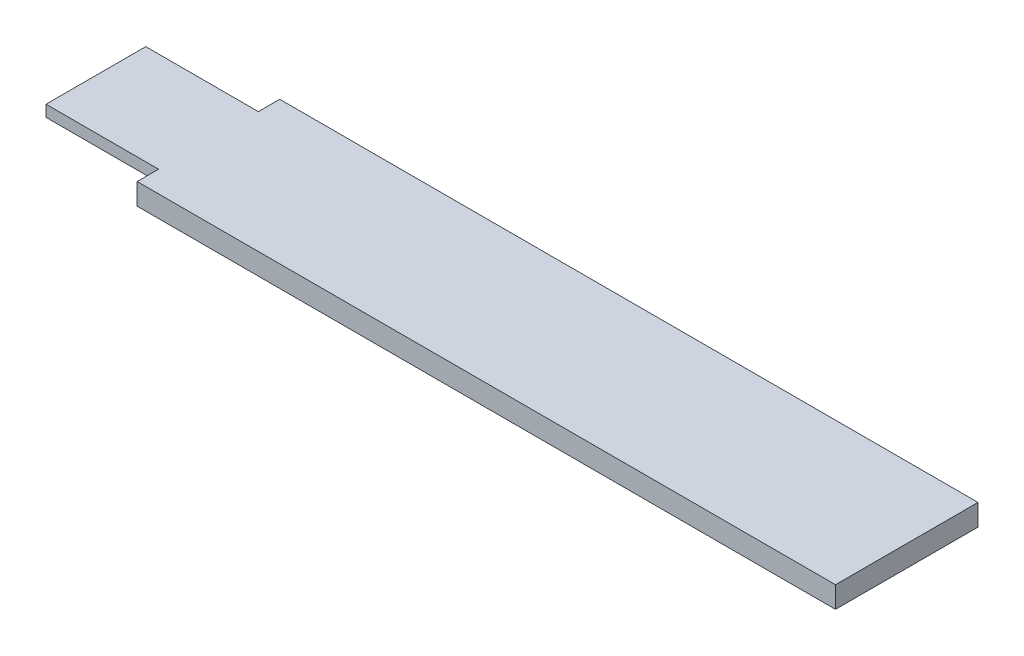
SolidWorks part; units mm, degrees
ref_plane "前视基准面" through (0, 0, 0) normal (0, 0, 1) x (1, 0, 0)
ref_plane "上视基准面" through (0, 0, 0) normal (0, 1, 0) x (1, 0, 0)
ref_plane "右视基准面" through (0, 0, 0) normal (1, 0, 0) x (0, 0, -1)
ref_plane "基准面4" through (0, 0, 0) normal (0, -1, 0) x (1, 0, 0)
sketch "草图1" plane through (0, 0, 0) normal (0, -1, 0) x (1, 0, 0)
  line L0 (245, -50) -> (245, 50)
  line L1 (245, 50) -> (-245, 50)
  line L2 (-245, 50) -> (-245, 35)
  line L3 (-245, 35) -> (-235, 35)
  line L4 (-235, 35) -> (-235, -35)
  line L5 (-235, -35) -> (-245, -35)
  line L6 (-245, -35) -> (-245, -50)
  line L7 (-245, -50) -> (245, -50)
extrude "凸台-拉伸1" add sketch "草图1" against normal blind 15
sketch "草图2" plane through (-235, 0, 0) normal (-1, 0, 0) x (0, 0, 1)
  line L10 (-26.3009, 7) -> (-35, 7)
  line L11 (-26.3009, 7) -> (35, 7)
  line L12 (35, 15) -> (35, 0) construction
  line L13 (35, 7) -> (35, 15)
  line L14 (35, 15) -> (-35, 15)
  line L15 (-35, 15) -> (-35, 7)
extrude "凸台-拉伸3" add sketch "草图2" along normal blind 89
